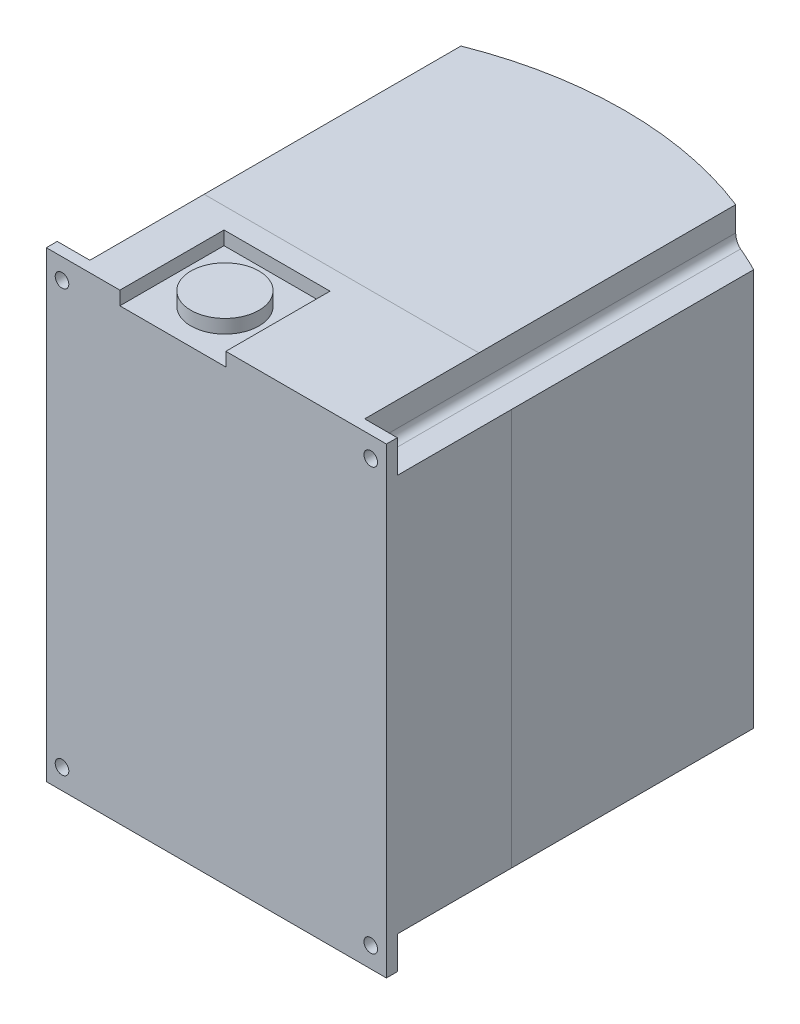
SolidWorks part; units mm, degrees
ref_plane "Front Plane" through (0, 0, 0) normal (0, 0, 1) x (1, 0, 0)
ref_plane "Top Plane" through (0, 0, 0) normal (0, 1, 0) x (1, 0, 0)
ref_plane "Right Plane" through (0, 0, 0) normal (1, 0, 0) x (0, 0, -1)
sketch "Sketch1" plane through (0, 0, 0) normal (1, 0, 0) x (0, 0, -1)
  line L1 (-75, -85) -> (75, -85)
  line L2 (-75, -85) -> (-75, 85)
  line L3 (-75, 85) -> (75, 85)
  line L4 (75, -85) -> (75, 85)
  line L5 (-75, -85) -> (75, 85) construction
  line L6 (-75, 85) -> (75, -85) construction
  point P0 (0, 0)
  dimension "D1" = 170
  dimension "D2" = 150
extrude "Boss-Extrude1" add sketch "Sketch1" along normal mid plane 125
sketch "Sketch2" plane through (0, 85, 0) normal (0, 1, 0) x (1, 0, 0)
  line L0 (-62.5, 75) -> (-62.5, -75) construction
  line L1 (62.5, 75) -> (62.5, -75) construction
  line L2 (62.5, -75) -> (-62.5, -75) construction
  line L3 (0, 0) -> (0, 147.7344) construction
  line L4 (62.5, 75) -> (-62.5, 75) construction
  arc A0 (-62.5, 60) -> (62.5, 60) centre (0, -62.7083) cw
  dimension "D1" = 135
extrude "Cut-Extrude1" cut sketch "Sketch2" against normal through all and the other way through all
sketch "Sketch3" plane through (0, 0, 75) normal (0, 0, 1) x (1, 0, 0)
  line L0 (0, 0) -> (0, 125.871) construction
  line L1 (50.5, 125.1382) -> (106.6216, 125.1382)
  line L2 (50.5, 125.1382) -> (50.5, 76)
  line L3 (53.5, 73) -> (106.6216, 73)
  line L4 (106.6216, 125.1382) -> (106.6216, 73)
  line L5 (50.5, 125.1382) -> (106.6216, 73) construction
  line L6 (50.5, 73) -> (106.6216, 125.1382) construction
  line L7 (0, 0) -> (94.5521, 0) construction
  line L8 (62.5, 85) -> (-62.5, 85) construction
  line L9 (62.5, 85) -> (62.5, -85) construction
  line L10 (-50.5, 73) -> (-106.6216, 125.1382) construction
  line L11 (-50.5, 125.1382) -> (-106.6216, 73) construction
  line L12 (-106.6216, 125.1382) -> (-106.6216, 73)
  line L13 (-53.5, 73) -> (-106.6216, 73)
  line L14 (-50.5, 125.1382) -> (-50.5, 76)
  line L15 (-50.5, 125.1382) -> (-106.6216, 125.1382)
  line L16 (-50.5, -125.1382) -> (-106.6216, -73) construction
  line L17 (-50.5, -73) -> (-106.6216, -125.1382) construction
  line L18 (50.5, -73) -> (106.6216, -125.1382) construction
  line L19 (50.5, -125.1382) -> (106.6216, -73) construction
  line L20 (-50.5, -125.1382) -> (-106.6216, -125.1382)
  line L21 (-50.5, -125.1382) -> (-50.5, -76)
  line L22 (-53.5, -73) -> (-106.6216, -73)
  line L23 (-106.6216, -125.1382) -> (-106.6216, -73)
  line L24 (106.6216, -125.1382) -> (106.6216, -73)
  line L25 (53.5, -73) -> (106.6216, -73)
  line L26 (50.5, -125.1382) -> (50.5, -76)
  line L27 (50.5, -125.1382) -> (106.6216, -125.1382)
  arc A0 (50.5, 76) -> (53.5, 73) centre (53.5, 76) ccw
  arc A1 (-50.5, 76) -> (-53.5, 73) centre (-53.5, 76) cw
  arc A2 (-50.5, -76) -> (-53.5, -73) centre (-53.5, -76) ccw
  arc A3 (50.5, -76) -> (53.5, -73) centre (53.5, -76) cw
  point P0 (78.5608, 99.0691)
  point P23 (-78.5608, 99.0691)
  point P38 (-78.5608, -99.0691)
  point P39 (78.5608, -99.0691)
  dimension "D3" = 3
  dimension "D1" = 12
  dimension "D2" = 12
extrude "Cut-Extrude2" cut sketch "Sketch3" against normal through all from offset 4 offset against normal yes
sketch "Sketch4" plane through (0, 0, 71) normal (0, 0, -1) x (-1, 0, 0)
  line L0 (0, 0) -> (-92.4867, 0) construction
  line L1 (0, 0) -> (0, 113.9489) construction
  circle A0 centre (-56.75, 77.5) radius 2.5
  circle A1 centre (56.75, 77.5) radius 2.5
  circle A2 centre (56.75, -77.5) radius 2.5
  circle A3 centre (-56.75, -77.5) radius 2.5
  dimension "D1" = 5
  dimension "D2" = 108.5
  dimension "D3" = 150
extrude "Cut-Extrude3" cut sketch "Sketch4" against normal through all
sketch "Sketch5" plane through (0, 0, 0) normal (0, 0, 1) x (1, 0, 0)
  line L0 (50.5, 85) -> (-50.5, 85) construction
  line L1 (27.5, 67) -> (-27.5, 67)
  line L2 (27.5, 67) -> (27.5, -9)
  line L3 (27.5, -9) -> (-27.5, -9)
  line L4 (-27.5, 67) -> (-27.5, -9)
  line L5 (27.5, 67) -> (-27.5, -9) construction
  line L6 (27.5, -9) -> (-27.5, 67) construction
  point P0 (0, 29)
  dimension "D1" = 18
  dimension "D2" = 55
  dimension "D3" = 76
split line "Split Line1"
sketch "Sketch6" plane through (0, 0, 0) normal (0, 0, 1) x (1, 0, 0)
  line L0 (50.5, 85) -> (-50.5, 85) construction
  line L1 (-62.5, 73) -> (-62.5, -73) construction
  circle A0 centre (-16.5, 25) radius 5
  dimension "D1" = 10
  dimension "D2" = 60
  dimension "D3" = 46
extrude "Boss-Extrude2" [suppressed] add sketch "Sketch6" against normal offset from surface (84.5516 mm away) 10
sketch "Sketch7" plane through (0, 85, 0) normal (0, 1, 0) x (1, 0, 0)
  line L0 (62.5, -75) -> (-62.5, -75) construction
  line L1 (-35.4755, -36.7093) -> (3.4809, -36.7093)
  line L2 (-35.4755, -36.7093) -> (-35.4755, -75)
  line L3 (-35.4755, -75) -> (3.4809, -75)
  line L4 (3.4809, -36.7093) -> (3.4809, -75)
  line L5 (-35.4755, -36.7093) -> (3.4809, -75) construction
  line L6 (-35.4755, -75) -> (3.4809, -36.7093) construction
  circle A0 centre (-15.9973, -55.8547) radius 12.5199
  point P0 (-15.9973, -55.8547)
extrude "Cut-Extrude4" cut sketch "Sketch7" against normal blind 5
sketch "Sketch8" plane through (-62.5, 0, 0) normal (-1, 0, 0) x (0, 0, 1)
  line L0 (29, -109.9316) -> (29, 157.0624)
  line L1 (75, 85) -> (75, -85) construction
  dimension "D1" = 46
split line "Split Line2"
